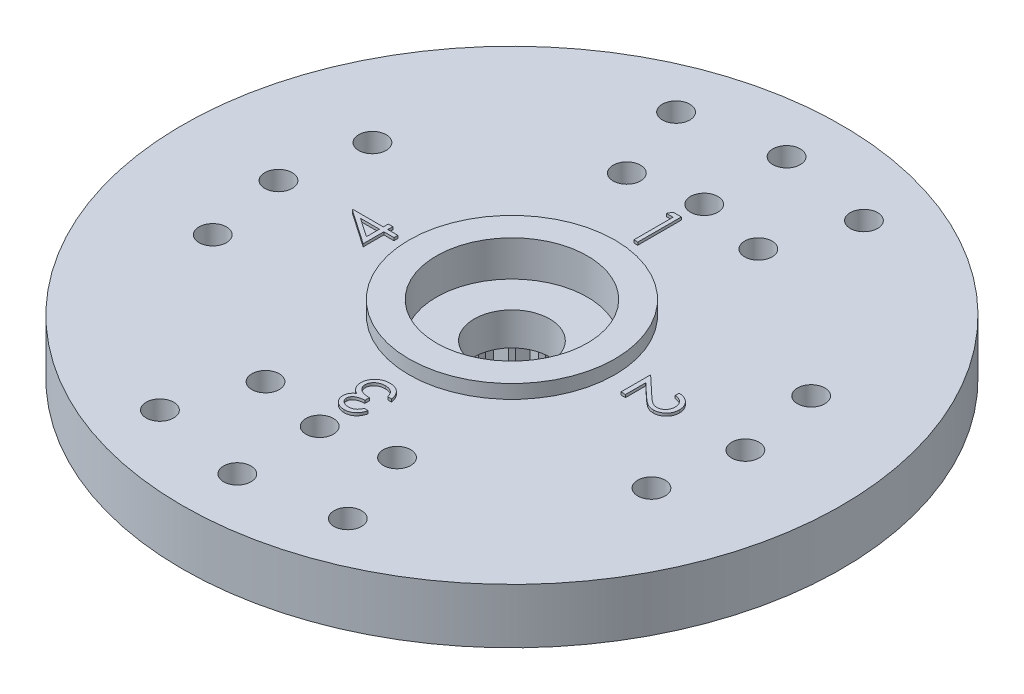
SolidWorks part; units mm, degrees
ref_plane "Front Plane" through (0, 0, 0) normal (0, 0, 1) x (1, 0, 0)
ref_plane "Top Plane" through (0, 0, 0) normal (0, 1, 0) x (1, 0, 0)
ref_plane "Right Plane" through (0, 0, 0) normal (1, 0, 0) x (0, 0, -1)
sketch "Sketch1" plane through (0, 0, 0) normal (0, 1, 0) x (1, 0, 0)
  line L0 (0, 12) -> (0, -12) construction
  line L1 (-12, 0) -> (12, 0) construction
  line L2 (0, 0) -> (3.4202, 9.3969) construction
  line L3 (-3.4202, 9.3969) -> (0, 0) construction
  line L4 (0, 0) -> (7.9874, 2.9072) construction
  line L5 (0, 0) -> (7.9874, -2.9072) construction
  circle A0 centre (0, 0) radius 12
  circle A1 centre (0, 0) radius 1.375
  circle A2 centre (0, 0) radius 7 construction
  circle A3 centre (0, 0) radius 10 construction
  circle A4 centre (0, 0) radius 8.5 construction
  circle A5 centre (0, 10) radius 0.5
  circle A6 centre (-3.4202, 9.3969) radius 0.5
  circle A7 centre (3.4202, 9.3969) radius 0.5
  circle A8 centre (0, 7) radius 0.5
  circle A9 centre (-2.3941, 6.5778) radius 0.5
  circle A10 centre (2.3941, 6.5778) radius 0.5
  circle A11 centre (8.5, 0) radius 0.5
  circle A12 centre (7.9874, 2.9072) radius 0.5
  circle A13 centre (7.9874, -2.9072) radius 0.5
  circle A14 centre (-2.3941, -6.5778) radius 0.5
  circle A15 centre (0, -7) radius 0.5
  circle A16 centre (2.3941, -6.5778) radius 0.5
  circle A17 centre (3.4202, -9.3969) radius 0.5
  circle A18 centre (0, -10) radius 0.5
  circle A19 centre (-3.4202, -9.3969) radius 0.5
  circle A20 centre (-7.9874, -2.9072) radius 0.5
  circle A21 centre (-8.5, 0) radius 0.5
  circle A22 centre (-7.9874, 2.9072) radius 0.5
  dimension "D1" = 24
  dimension "D2" = 2.75
  dimension "D3" = 14
  dimension "D4" = 20
  dimension "D5" = 17
  dimension "D6" = 1
  dimension "D7" = 1
  dimension "D9" = 1
  dimension "D11" = 1
  dimension "D12" = 1
  dimension "D13" = 1
  dimension "D16" = 1
  dimension "D17" = 1
  dimension "D18" = 1
  dimension "D8" = 20
  dimension "D10" = 20
  dimension "D14" = 20
  dimension "D15" = 20
extrude "Boss-Extrude1" add sketch "Sketch1" along normal blind 2
sketch "Sketch2" plane through (0, 2, 0) normal (0, 1, 0) x (1, 0, 0)
  circle A0 centre (0, 0) radius 3.75
  circle A1 centre (0, 0) radius 2.75
  dimension "D1" = 7.5
  dimension "D2" = 1
extrude "Boss-Extrude2" add sketch "Sketch2" along normal blind 0.5
sketch "Sketch3" plane through (0, 2, 0) normal (0, 1, 0) x (1, 0, 0)
  circle A0 centre (0, 0) radius 1.375 construction
  circle A1 centre (0, 0) radius 2.75 construction
  circle A2 centre (0, 0) radius 1.375
  circle A3 centre (0, 0) radius 2.75
extrude "Cut-Extrude1" cut sketch "Sketch3" against normal blind 0.8
sketch "Sketch4" plane through (0, 0, 0) normal (0, -1, 0) x (1, 0, 0)
  circle A0 centre (0, 0) radius 4.5
  circle A1 centre (0, 0) radius 2.5
  dimension "D1" = 9
  dimension "D2" = 2
extrude "Boss-Extrude3" add sketch "Sketch4" along normal blind 2.5
sketch "Sketch5" plane through (0, -2.5, 0) normal (0, -1, 0) x (1, 0, 0)
  line L0 (0, 0) -> (0, 0.6245) construction
  line L1 (0, 3) -> (-0.299, 2.4821)
  line L2 (0, 3) -> (0.299, 2.4821)
  line L3 (0.9271, 2.8532) -> (0.4826, 2.453)
  line L4 (0.9271, 2.8532) -> (1.0514, 2.2682)
  line L5 (1.7634, 2.4271) -> (1.217, 2.1838)
  line L6 (1.7634, 2.4271) -> (1.7008, 1.8323)
  line L7 (2.4271, 1.7634) -> (1.8323, 1.7008)
  line L8 (2.4271, 1.7634) -> (2.1838, 1.217)
  line L9 (2.8532, 0.9271) -> (2.2682, 1.0514)
  line L10 (2.8532, 0.9271) -> (2.453, 0.4826)
  line L11 (3, 0) -> (2.4821, 0.299)
  line L12 (3, 0) -> (2.4821, -0.299)
  line L13 (2.8532, -0.9271) -> (2.453, -0.4826)
  line L14 (2.8532, -0.9271) -> (2.2682, -1.0514)
  line L15 (2.4271, -1.7634) -> (2.1838, -1.217)
  line L16 (2.4271, -1.7634) -> (1.8323, -1.7008)
  line L17 (1.7634, -2.4271) -> (1.7008, -1.8323)
  line L18 (1.7634, -2.4271) -> (1.217, -2.1838)
  line L19 (0.9271, -2.8532) -> (1.0514, -2.2682)
  line L20 (0.9271, -2.8532) -> (0.4826, -2.453)
  line L21 (0, -3) -> (0.299, -2.4821)
  line L22 (0, -3) -> (-0.299, -2.4821)
  line L23 (-0.9271, -2.8532) -> (-0.4826, -2.453)
  line L24 (-0.9271, -2.8532) -> (-1.0514, -2.2682)
  line L25 (-1.7634, -2.4271) -> (-1.217, -2.1838)
  line L26 (-1.7634, -2.4271) -> (-1.7008, -1.8323)
  line L27 (-2.4271, -1.7634) -> (-1.8323, -1.7008)
  line L28 (-2.4271, -1.7634) -> (-2.1838, -1.217)
  line L29 (-2.8532, -0.9271) -> (-2.2682, -1.0514)
  line L30 (-2.8532, -0.9271) -> (-2.453, -0.4826)
  line L31 (-3, 0) -> (-2.4821, -0.299)
  line L32 (-3, 0) -> (-2.4821, 0.299)
  line L33 (-2.8532, 0.9271) -> (-2.453, 0.4826)
  line L34 (-2.8532, 0.9271) -> (-2.2682, 1.0514)
  line L35 (-2.4271, 1.7634) -> (-2.1838, 1.217)
  line L36 (-2.4271, 1.7634) -> (-1.8323, 1.7008)
  line L37 (-1.7634, 2.4271) -> (-1.7008, 1.8323)
  line L38 (-1.7634, 2.4271) -> (-1.217, 2.1838)
  line L39 (-0.9271, 2.8532) -> (-1.0514, 2.2682)
  line L40 (-0.9271, 2.8532) -> (-0.4826, 2.453)
  circle A0 centre (0, 0) radius 2.5 construction
  arc A1 (-2.1838, 1.217) -> (-2.2682, 1.0514) centre (0, 0) ccw
  arc A2 (-1.7008, 1.8323) -> (-1.8323, 1.7008) centre (0, 0) ccw
  arc A3 (-1.0514, 2.2682) -> (-1.217, 2.1838) centre (0, 0) ccw
  arc A4 (-0.299, 2.4821) -> (-0.4826, 2.453) centre (0, 0) ccw
  arc A5 (0.4826, 2.453) -> (0.299, 2.4821) centre (0, 0) ccw
  arc A6 (1.217, 2.1838) -> (1.0514, 2.2682) centre (0, 0) ccw
  arc A7 (1.8323, 1.7008) -> (1.7008, 1.8323) centre (0, 0) ccw
  arc A8 (2.2682, 1.0514) -> (2.1838, 1.217) centre (0, 0) ccw
  arc A9 (2.4821, 0.299) -> (2.453, 0.4826) centre (0, 0) ccw
  arc A10 (2.453, -0.4826) -> (2.4821, -0.299) centre (0, 0) ccw
  arc A11 (2.1838, -1.217) -> (2.2682, -1.0514) centre (0, 0) ccw
  arc A12 (1.7008, -1.8323) -> (1.8323, -1.7008) centre (0, 0) ccw
  arc A13 (1.0514, -2.2682) -> (1.217, -2.1838) centre (0, 0) ccw
  arc A14 (0.299, -2.4821) -> (0.4826, -2.453) centre (0, 0) ccw
  arc A15 (-0.4826, -2.453) -> (0, -2.5) centre (0, 0) ccw
  arc A16 (-1.217, -2.1838) -> (-1.0514, -2.2682) centre (0, 0) ccw
  arc A17 (-1.8323, -1.7008) -> (-1.7008, -1.8323) centre (0, 0) ccw
  arc A18 (-2.2682, -1.0514) -> (-2.1838, -1.217) centre (0, 0) ccw
  arc A19 (-2.4821, -0.299) -> (-2.453, -0.4826) centre (0, 0) ccw
  arc A20 (-2.453, 0.4826) -> (-2.4821, 0.299) centre (0, 0) ccw
  point P68 (0, 0)
  circle M5 centre (0, 0) radius 2.5
  dimension "D1" = 30
  dimension "D2" = 3
  dimension "D3" = 20
extrude "Cut-Extrude3" cut sketch "Sketch5" against normal up to surface (2.5 mm away) contours L36 L35 M5 | L34 L33 M5 | L32 L31 M5 | L30 L29 M5 | L28 L27 M5 | L26 L25 M5 | L24 L23 M5 | L0 L21 M5 | L22 L0 M5 | L20 L19 M5 | L18 L17 M5 | L16 L15 M5 | L14 L13 M5 | L12 L11 M5 | L10 L9 M5 | L8 L7 M5 | L6 L5 M5 | L4 L3 M5 | L0 L2 M5 | L0 L1 M5 | L40 L39 M5 | L38 L37 M5
sketch "Sketch6" plane through (0, 2, 0) normal (0, 1, 0) x (1, 0, 0)
  line L1 (4.5, -4.5) -> (-4.5, -4.5) construction
  line L2 (4.5, -4.5) -> (4.5, 4.5) construction
  line L3 (4.5, 4.5) -> (-4.5, 4.5) construction
  line L4 (-4.5, -4.5) -> (-4.5, 4.5) construction
  line L5 (4.5, -4.5) -> (-4.5, 4.5) construction
  line L6 (4.5, 4.5) -> (-4.5, -4.5) construction
  circle A0 centre (0, 0) radius 4.5 construction
  text T0 "1" font "Century Gothic" height in points 6
  text T1 "2" font "Century Gothic" height in points 6
  text T2 "3" font "Century Gothic" height in points 6
  text T3 "4" font "Century Gothic" height in points 6
  dimension "D1" = 9
  dimension "D2" = 9
  dimension "D3" = 9
extrude "Boss-Extrude4" add sketch "Sketch6" along normal blind 0.1
